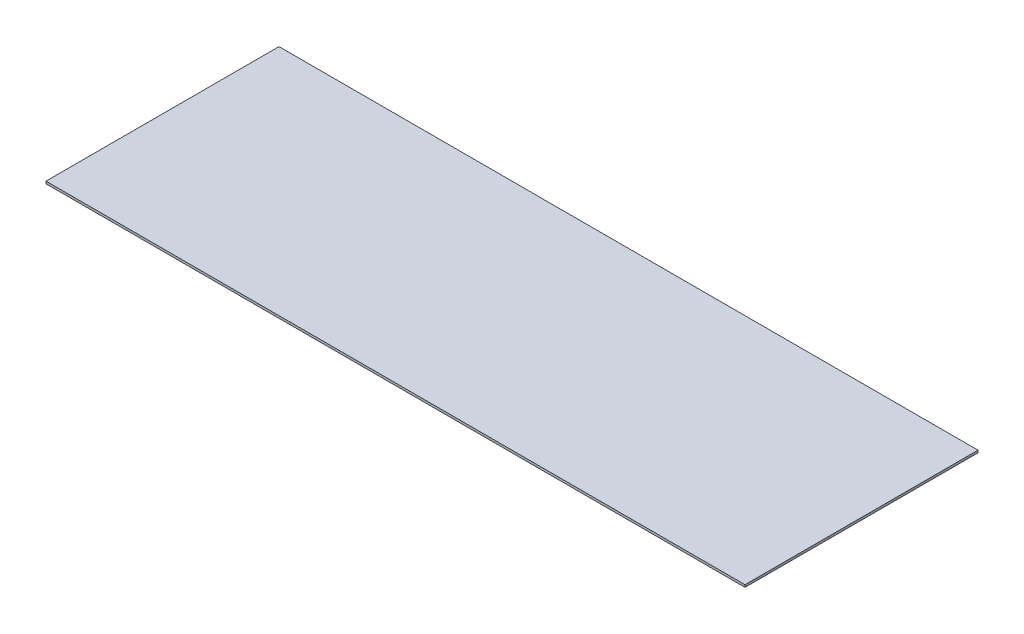
SolidWorks part; units mm, degrees
ref_plane "Front Plane" through (0, 0, 0) normal (0, 0, 1) x (1, 0, 0)
ref_plane "Top Plane" through (0, 0, 0) normal (0, 1, 0) x (1, 0, 0)
ref_plane "Right Plane" through (0, 0, 0) normal (1, 0, 0) x (0, 0, -1)
sketch "Sketch1" plane through (0, 0, 0) normal (0, 1, 0) x (1, 0, 0)
  line L1 (-150, 50) -> (150, 50)
  line L2 (-150, 50) -> (-150, -50)
  line L3 (-150, -50) -> (150, -50)
  line L4 (150, 50) -> (150, -50)
  line L5 (-150, 50) -> (150, -50) construction
  line L6 (-150, -50) -> (150, 50) construction
  point P0 (0, 0)
  dimension "D1" = 300
  dimension "D2" = 100
extrude "Boss-Extrude4" add sketch "Sketch1" along normal blind 1
